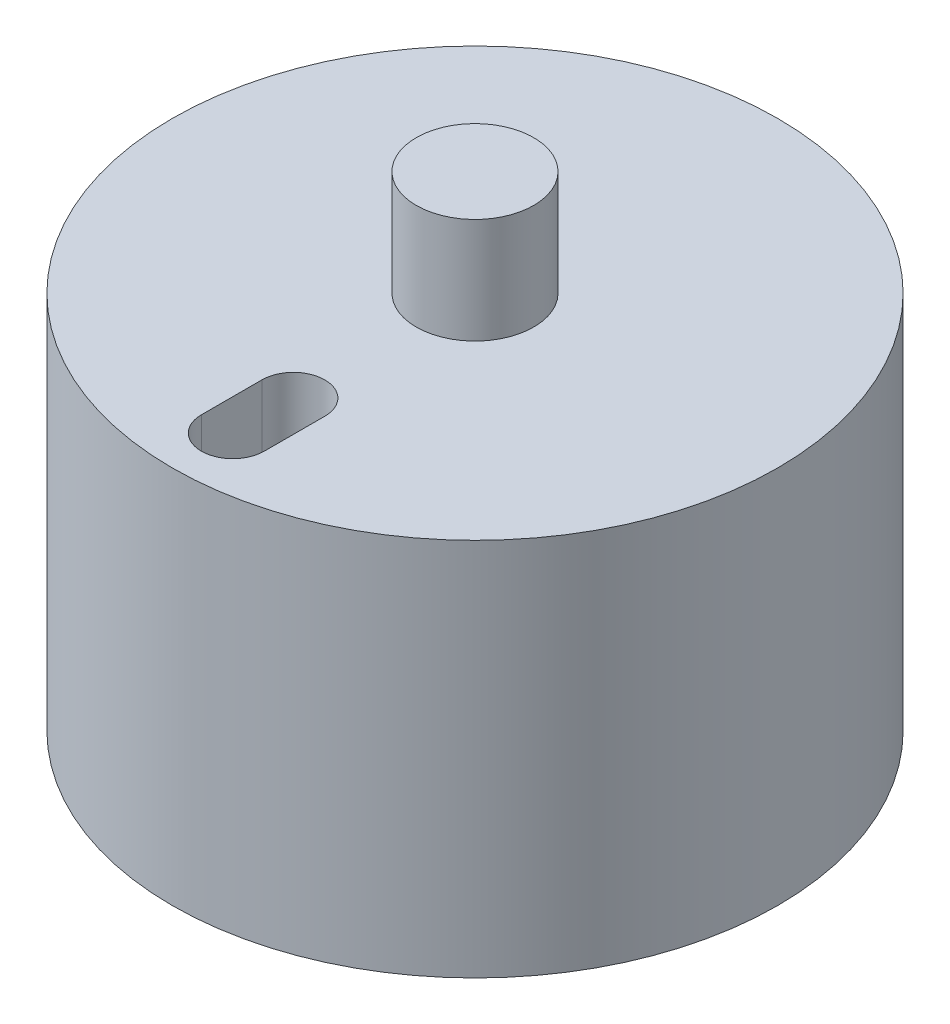
SolidWorks part; units mm, degrees
ref_plane "Front Plane" through (0, 0, 0) normal (0, 0, 1) x (1, 0, 0)
ref_plane "Top Plane" through (0, 0, 0) normal (0, 1, 0) x (1, 0, 0)
ref_plane "Right Plane" through (0, 0, 0) normal (1, 0, 0) x (0, 0, -1)
sketch "Sketch1" plane through (0, 0, 0) normal (0, 1, 0) x (1, 0, 0)
  circle A0 centre (0, 0) radius 25
  dimension "D1" = 50
extrude "Boss-Extrude1" add sketch "Sketch1" along normal blind 40
sketch "Sketch2" plane through (0, 40, 0) normal (0, 1, 0) x (1, 0, 0)
  circle A0 centre (0, 0) radius 25
  circle A1 centre (0, 0) radius 4.85
  dimension "D1" = 50
  dimension "D2" = 9.7
extrude "Cut-Extrude1" cut sketch "Sketch2" against normal blind 8.7
sketch "Sketch3" plane through (0, 31.3, 0) normal (0, 1, 0) x (1, 0, 0)
  line L0 (-2.6, -15) -> (-2.6, -20)
  line L1 (2.6, -15) -> (2.6, -20)
  line L2 (-2.6, -17.5) -> (2.6, -17.5) construction
  arc A0 (2.6, -15) -> (-2.6, -15) centre (0, -15) ccw
  arc A1 (-2.6, -20) -> (2.6, -20) centre (0, -20) ccw
  point P7 (0, -17.5)
  dimension "D1" = 5.2
  dimension "D2" = 5
  dimension "D3" = 15
extrude "Cut-Extrude2" cut sketch "Sketch3" against normal blind 10
sketch "Sketch5" plane through (0, 21.3, 0) normal (0, 1, 0) x (1, 0, 0)
  circle A0 centre (0, -17.5) radius 1.5
  point P2 (0, 0)
  point P3 (0, 0)
  dimension "D1" = 3
extrude "Cut-Extrude3" cut sketch "Sketch5" against normal through all
